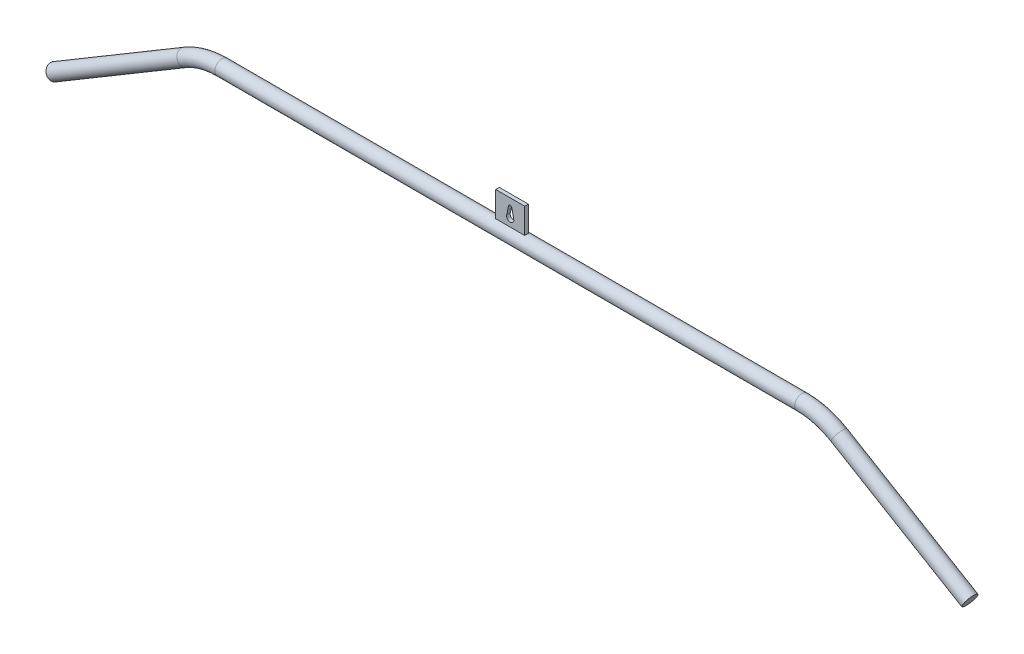
SolidWorks part; units mm, degrees
ref_plane "Front Plane" through (0, 0, 0) normal (0, 0, 1) x (1, 0, 0)
ref_plane "Top Plane" through (0, 0, 0) normal (0, 1, 0) x (1, 0, 0)
ref_plane "Right Plane" through (0, 0, 0) normal (1, 0, 0) x (0, 0, -1)
sketch "Sketch1" plane through (0, 0, 0) normal (0, 0, 1) x (1, 0, 0)
  line L0 (0, -55) -> (0, 55) construction
  line L2 (0, 1.5438) -> (400, 1.5438)
  line L3 (451.1534, -12.5299) -> (631.5986, -119.9521)
  arc A0 (400, 1.5438) -> (451.1534, -12.5299) centre (400, -98.4562) cw
  dimension "D1" = 100
  dimension "D2" = 0
  dimension "D4" = 400
  dimension "D5" = 210
sketch "Sketch2" plane through (0, 0, 0) normal (1, 0, 0) x (0, 0, -1)
  circle A0 centre (0, 1.5438) radius 10
  dimension "D1" = 20
sweep "Sweep1" add profiles "Sketch2" path "Sketch1"
mirror "Mirror1" about plane through (0, 1.5438, 0) normal (1, 0, 0) of bodies 101
sketch "Sketch3" plane through (0, 0, 0) normal (0, 0, 1) x (1, 0, 0)
  line L0 (20, 11.5438) -> (-20, 11.5438) construction
  line L1 (400, 11.5438) -> (-400, 11.5438) construction
  line L2 (-20, 46.5438) -> (-20, 11.5438)
  line L3 (20, 46.5438) -> (20, 11.5438)
  line L5 (-0.4625, 3.6191) -> (-0.429, 3.7918)
  line L6 (0.4625, 3.6191) -> (0.429, 3.7918)
  line L7 (-20, 11.5438) -> (20, 11.5438)
  line L8 (-20, 46.5438) -> (0, 29.0438) construction
  line L9 (-20, 11.5438) -> (-3.7133, 25.7947) construction
  line L10 (20, 46.5438) -> (-20, 46.5438)
  line L11 (-4.6199, 24.3559) -> (-2.5205, 34.95)
  line L12 (2.5205, 34.95) -> (4.6199, 24.3559)
  line L13 (0, 29.0438) -> (20, 46.5438) construction
  line L14 (4.4651, 25.1369) -> (20, 11.5438) construction
  arc A0 (-0.429, 3.7918) -> (-0.4625, 3.6191) centre (0, 3.6191) ccw
  arc A1 (0.2457, 4.7381) -> (-0.2457, 4.7381) centre (0, 4.7381) ccw
  arc A2 (-4.6199, 24.3559) -> (4.6199, 24.3559) centre (0, 22.45) ccw
  arc A3 (2.5205, 34.95) -> (-2.5205, 34.95) centre (0, 34.95) ccw
  arc A4 (0.4625, 3.6191) -> (0.429, 3.7918) centre (0, 3.6191) ccw
  point P0 (0, 29.0438)
  point P5 (0, 11.5438)
  point P6 (0, 11.5438)
  dimension "D1" = 35
  dimension "D2" = 40
  dimension "D3" = 0
  dimension "D4" = 12.5
extrude "Boss-Extrude1" add sketch "Sketch3" along normal mid plane 5 separate body contours L3 L10 L2 L7 A3 L12 A2 L11
